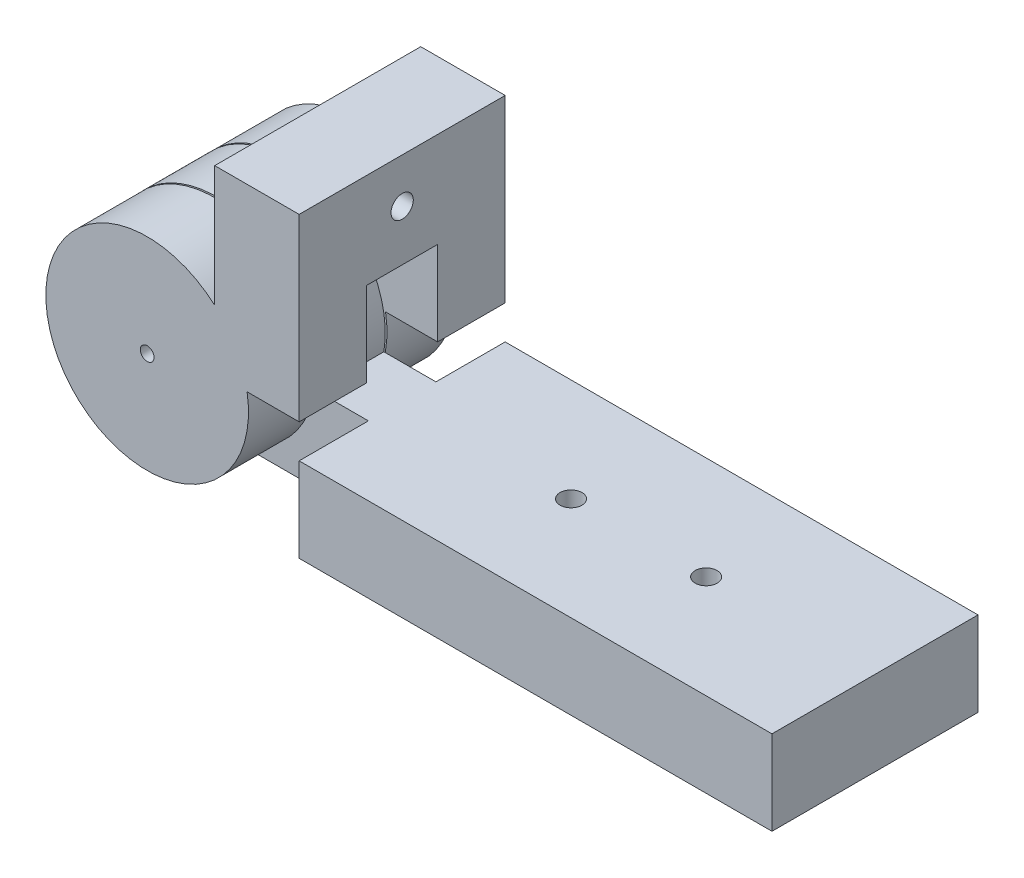
SolidWorks part; units mm, degrees
ref_plane "Front Plane" through (0, 0, 0) normal (0, 0, 1) x (1, 0, 0)
ref_plane "Top Plane" through (0, 0, 0) normal (0, 1, 0) x (1, 0, 0)
ref_plane "Right Plane" through (0, 0, 0) normal (1, 0, 0) x (0, 0, -1)
sketch "Sketch1" plane through (0, 0, 0) normal (0, 0, 1) x (1, 0, 0)
  circle A0 centre (-73.025, -41.275) radius 19.05
  circle A2 centre (-73.025, -41.275) radius 2.8702 construction
  dimension "D1" = 38.1
extrude "Boss-Extrude1" add sketch "Sketch1" along normal mid plane 12.7
sketch "Sketch2" plane through (0, 0, 6.35) normal (0, 0, 1) x (1, 0, 0)
  line L0 (-54.2414, -44.45) -> (44.45, -44.45)
  line L1 (44.45, -44.45) -> (44.45, -60.325)
  line L2 (44.45, -60.325) -> (-73.025, -60.325)
  line L3 (44.45, -44.45) -> (-44.45, -44.45) construction
  line L5 (44.45, 38.1) -> (44.45, -38.1) construction
  circle A0 centre (-73.025, -41.275) radius 19.05 construction
  arc A1 (-73.025, -60.325) -> (-54.2414, -44.45) centre (-73.025, -41.275) ccw
extrude "Boss-Extrude2" add sketch "Sketch2" against normal up to surface (12.7 mm away) up to face at (-53.975, -41.275, -6.35)
sketch "Sketch3" plane through (0, 0, 6.35) normal (0, 0, 1) x (1, 0, 0)
  circle A0 centre (-73.025, -41.275) radius 6.35
  dimension "D1" = 12.7
extrude "Cut-Extrude1" cut sketch "Sketch3" against normal through all
sketch "Sketch4" plane through (0, 0, 0) normal (0, 0, 1) x (1, 0, 0)
  circle A0 centre (-73.025, -41.275) radius 5.715
  dimension "D1" = 11.43
extrude "Boss-Extrude3" add sketch "Sketch4" against normal mid plane 13.335 separate body
sketch "Sketch5" plane through (0, 0, 6.6675) normal (0, 0, 1) x (1, 0, 0)
  circle A0 centre (-73.025, -41.275) radius 19.05
  arc A1 (-54.2414, -44.45) -> (-73.025, -60.325) centre (-73.025, -41.275) ccw construction
extrude "Boss-Extrude4" add sketch "Sketch5" along normal blind 12.7
sketch "Sketch6" plane through (0, 0, 19.3675) normal (0, 0, 1) x (1, 0, 0)
  line L0 (-44.45, -38.1) -> (-44.45, 38.1)
  line L1 (-44.45, 38.1) -> (-44.45, 24.5485) construction
  line L2 (-44.45, 38.1) -> (-60.325, 38.1)
  line L3 (-60.325, 38.1) -> (-60.325, -27.076)
  line L4 (-44.45, -38.1) -> (-54.2414, -38.1)
  line L5 (-44.45, -38.1) -> (44.45, -38.1) construction
  circle A1 centre (-73.025, -41.275) radius 19.05 construction
  arc A2 (-60.325, -27.076) -> (-54.2414, -38.1) centre (-73.025, -41.275) cw
  dimension "D1" = 15.875
extrude "Boss-Extrude5" add sketch "Sketch6" against normal up to surface (12.7 mm away) up to face at (-67.31, -41.275, 6.6675)
ref_plane "Silo Hinge Mid Plane" through (0, 0, 0) normal (0, 0, 1) x (1, 0, 0)
mirror "Mirror1" about plane through (0, 0, 0) normal (0, 0, 1) of "Boss-Extrude5", "Boss-Extrude4"
sketch "Sketch7" plane through (0, 0, 6.6675) normal (0, 0, -1) x (-1, 0, 0)
  line L0 (60.325, -27.076) -> (60.325, 38.1) construction
  line L1 (44.45, 38.1) -> (60.325, 38.1)
  line L2 (44.45, 38.1) -> (44.45, -22.225)
  line L3 (44.45, -22.225) -> (60.325, -22.225)
  line L4 (60.325, 38.1) -> (60.325, -22.225)
  line L5 (98.7602, -22.225) -> (64.3668, -22.225) construction
  arc A0 (54.2414, -38.1) -> (60.325, -27.076) centre (73.025, -41.275) ccw construction
extrude "Boss-Extrude6" add sketch "Sketch7" along normal up to surface (13.335 mm away)
sketch "Sketch8" plane through (0, 0, 6.35) normal (0, 0, 1) x (1, 0, 0)
  line L0 (44.45, -44.45) -> (-54.2414, -44.45) construction
  line L1 (44.45, -60.325) -> (-44.45, -60.325)
  line L2 (44.45, -60.325) -> (44.45, -44.45)
  line L3 (44.45, -44.45) -> (-44.45, -44.45)
  line L4 (-44.45, -60.325) -> (-44.45, -44.45)
extrude "Boss-Extrude7" add sketch "Sketch8" along normal up to surface and the other way up to surface
sketch "Sketch9" [suppressed] plane through (0, 0, -6.35) normal (0, 0, -1) x (-1, 0, 0)
  line L4 (60.325, -27.076) -> (60.325, 38.1)
  line L5 (60.325, 38.1) -> (44.45, 38.1)
  line L6 (44.45, 38.1) -> (44.45, -38.1)
  line L7 (44.45, -38.1) -> (54.2414, -38.1)
  line L8 (60.325, -27.076) -> (60.325, 38.1)
  line L9 (60.325, 38.1) -> (44.45, 38.1)
  line L10 (44.45, 38.1) -> (44.45, -38.1)
  line L11 (44.45, -38.1) -> (54.2414, -38.1)
  arc A1 (54.2414, -38.1) -> (60.325, -27.076) centre (73.025, -41.275) ccw
  arc A2 (54.2414, -38.1) -> (60.325, -27.076) centre (73.025, -41.275) ccw
  dimension "D1" = 0
extrude "Cut-Extrude2" [suppressed] cut sketch "Sketch9" along normal through all
mirror "Mirror2" [suppressed] about plane through (0, 0, 0) normal (0, 0, 1)
sketch "Sketch10" [suppressed] plane through (0, 0, -6.35) normal (0, 0, -1) x (-1, 0, 0)
  line L1 (44.45, 38.1) -> (60.325, 38.1)
  line L2 (44.45, 38.1) -> (44.45, -22.225)
  line L3 (44.45, -22.225) -> (60.325, -22.225)
  line L4 (60.325, 38.1) -> (60.325, -22.225)
extrude "Cut-Extrude3" [suppressed] cut sketch "Sketch10" against normal through all
sketch "Sketch11" [suppressed] plane through (0, 0, -6.35) normal (0, 0, -1) x (-1, 0, 0)
  circle A0 centre (73.025, -41.275) radius 6.0275
extrude "Cut-Extrude4" [suppressed] cut sketch "Sketch11" against normal through all
sketch "Sketch12" [suppressed] plane through (0, 0, -6.35) normal (0, 0, -1) x (-1, 0, 0)
  circle A0 centre (73.025, -41.275) radius 6.35
  circle A1 centre (73.025, -41.275) radius 1.5875
  circle A2 centre (73.025, -41.275) radius 6.35 construction
  dimension "D1" = 3.175
extrude "Boss-Extrude8" [suppressed] add sketch "Sketch12" against normal up to surface (12.7 mm away)
sketch "Sketch13" [suppressed] plane through (0, 0, -6.35) normal (0, 0, -1) x (-1, 0, 0)
  line L0 (54.2414, -44.45) -> (44.45, -44.45) construction
  line L1 (44.45, -44.45) -> (44.45, -60.325) construction
  line L2 (44.45, -60.325) -> (73.025, -60.325) construction
  line L3 (54.2414, -44.45) -> (44.45, -44.45)
  line L4 (44.45, -44.45) -> (44.45, -60.325)
  line L5 (44.45, -60.325) -> (73.025, -60.325)
  arc A0 (54.2414, -38.1) -> (60.325, -27.076) centre (73.025, -41.275) ccw construction
  arc A1 (54.2414, -38.1) -> (60.325, -27.076) centre (73.025, -41.275) ccw
  arc A2 (60.325, -27.076) -> (54.2414, -38.1) centre (73.025, -41.275) ccw
extrude "Cut-Extrude5" [suppressed] cut sketch "Sketch13" against normal up to surface and the other way up to surface
sketch "Sketch14" [suppressed] plane through (0, 0, -19.3675) normal (0, 0, -1) x (-1, 0, 0)
  line L1 (-44.45, -44.45) -> (44.45, -44.45)
  line L2 (-44.45, -44.45) -> (-44.45, -60.325)
  line L3 (-44.45, -60.325) -> (44.45, -60.325)
  line L4 (44.45, -44.45) -> (44.45, -60.325)
extrude "Cut-Extrude6" [suppressed] cut sketch "Sketch14" against normal through all
sketch "Sketch15" [suppressed] plane through (0, 0, -19.3675) normal (0, 0, -1) x (-1, 0, 0)
  circle A0 centre (73.025, -41.275) radius 1.5875
  arc A1 (54.2414, -38.1) -> (60.325, -27.076) centre (73.025, -41.275) ccw construction
  dimension "D1" = 3.175
extrude "Cut-Extrude7" [suppressed] cut sketch "Sketch15" against normal through all
sketch "Sketch16" plane through (-60.325, 0, 0) normal (-1, 0, 0) x (0, 0, 1)
  line L0 (0, -20.955) -> (0, 20.955) construction
  line L1 (0, 0) -> (0, 48.408) construction
  line L2 (0, 0) -> (40.8974, 0) construction
  circle A0 centre (0, 12.7) radius 2.0955
  circle A1 centre (0, -12.7) radius 2.0955
  dimension "D1" = 4.191
  dimension "D2" = 25.4
extrude "Cut-Extrude8" cut sketch "Sketch16" against normal through all
sketch "Sketch17" plane through (0, -44.45, 0) normal (0, 1, 0) x (1, 0, 0)
  line L0 (0, 0) -> (0, 11.213) construction
  line L2 (0, 0) -> (4.8614, 0) construction
  circle A0 centre (-12.7, 0) radius 2.0638
  circle A1 centre (12.7, 0) radius 2.0638
  dimension "D1" = 4.1275
  dimension "D2" = 25.4
extrude "Cut-Extrude9" cut sketch "Sketch17" against normal through all
fillet "Fillet1" [suppressed] radius 1.27
fillet "Fillet2" [suppressed] radius 1.27
sketch "Sketch20" plane through (-60.325, 0, 0) normal (-1, 0, 0) x (0, 0, 1)
  line L0 (19.3675, 38.1) -> (19.3675, -27.076) construction
  line L1 (-19.3675, 38.1) -> (19.3675, 38.1)
  line L2 (-19.3675, 38.1) -> (-19.3675, -4.318)
  line L3 (-19.3675, -4.318) -> (19.3675, -4.318)
  line L4 (19.3675, 38.1) -> (19.3675, -4.318)
  dimension "D1" = 42.418
extrude "Cut-Extrude12" cut sketch "Sketch20" against normal through all
sketch "Sketch21" plane through (0, 0, 19.3675) normal (0, 0, 1) x (1, 0, 0)
  circle A0 centre (-73.025, -41.275) radius 1.2881
extrude "Cut-Extrude13" cut sketch "Sketch21" against normal through all
